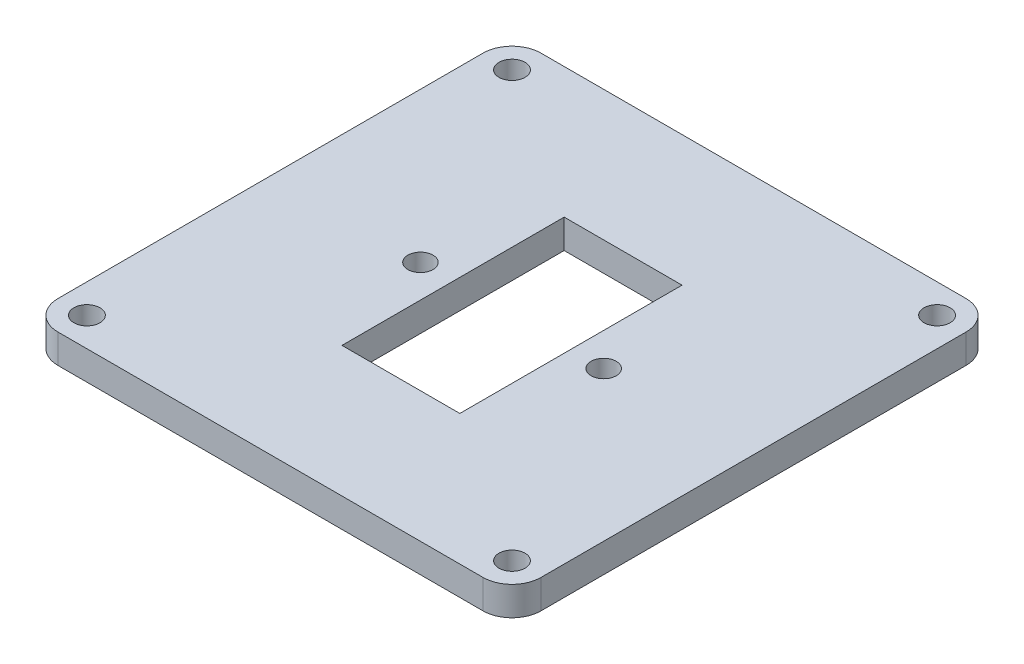
SolidWorks part; units mm, degrees
ref_plane "前视基准面" through (0, 0, 0) normal (0, 0, 1) x (1, 0, 0)
ref_plane "上视基准面" through (0, 0, 0) normal (0, 1, 0) x (1, 0, 0)
ref_plane "右视基准面" through (0, 0, 0) normal (1, 0, 0) x (0, 0, -1)
ref_plane "基准面1" through (0, -0.9062, 0) normal (0, -1, 0) x (1, 0, 0)
sketch "草图1" plane through (0, -0.9062, 0) normal (0, -1, 0) x (1, 0, 0)
  line L0 (-25.6485, 0) -> (18.3511, 0)
  line L1 (21.3511, 3) -> (21.3511, 46.9999)
  line L2 (18.3511, 49.9999) -> (-25.6485, 49.9999)
  line L3 (-28.6485, 46.9999) -> (-28.6485, 3)
  line L4 (-9.7487, 13.5002) -> (-9.7487, 36.5009)
  line L5 (-9.7487, 36.5009) -> (2.4517, 36.5009)
  line L6 (2.4517, 36.5009) -> (2.4517, 13.5002)
  line L7 (2.4517, 13.5002) -> (-9.7487, 13.5002)
  arc A0 (18.3511, 0) -> (21.3511, 3) centre (18.3511, 3) ccw
  arc A1 (21.3511, 46.9999) -> (18.3511, 49.9999) centre (18.3511, 46.9999) ccw
  arc A2 (-25.6485, 49.9999) -> (-28.6485, 46.9999) centre (-25.6485, 46.9999) ccw
  arc A3 (-28.6485, 3) -> (-25.6485, 0) centre (-25.6485, 3) ccw
  circle A4 centre (18.3511, 46.9999) radius 1.35
  circle A5 centre (-25.6485, 3) radius 1.35
  circle A6 centre (-25.6485, 46.9999) radius 1.35
  circle A7 centre (18.3511, 3) radius 1.35
  circle A8 centre (5.8705, 25.0265) radius 1.3
  circle A9 centre (-13.1299, 24.9945) radius 1.3
extrude "凸台-拉伸1" add sketch "草图1" against normal blind 3
